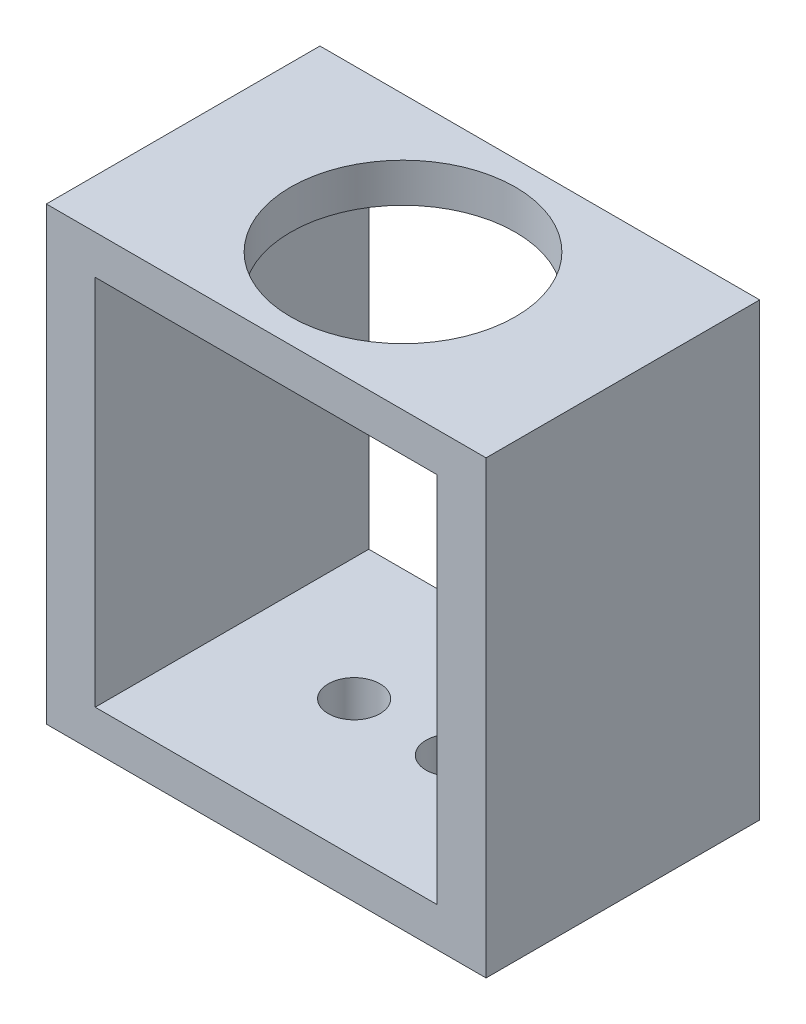
SolidWorks part; units mm, degrees
ref_plane "Front Plane" through (0, 0, 0) normal (0, 0, 1) x (1, 0, 0)
ref_plane "Top Plane" through (0, 0, 0) normal (0, 1, 0) x (1, 0, 0)
ref_plane "Right Plane" through (0, 0, 0) normal (1, 0, 0) x (0, 0, -1)
sketch "Sketch1" plane through (0, 0, 0) normal (0, 1, 0) x (1, 0, 0)
  line L0 (12.5, 14) -> (22.5, 14) construction
  line L1 (0, 0) -> (35, 0)
  line L2 (0, 0) -> (0, 28)
  line L3 (0, 28) -> (35, 28)
  line L4 (35, 0) -> (35, 28)
  line L5 (0, 14) -> (35, 14) construction
  line L6 (17.5, 28) -> (17.5, 0) construction
  circle A0 centre (12.5, 14) radius 2.65
  circle A1 centre (22.5, 14) radius 2.65
  dimension "D2" = 5.3
  dimension "D1" = 10
  dimension "D3" = 28
  dimension "D4" = 35
extrude "Boss-Extrude1" add sketch "Sketch1" along normal blind 4
sketch "Sketch2" plane through (0, 0, 0) normal (0, -1, 0) x (1, 0, 0)
  line L0 (35, -28) -> (0, -28) construction
  line L1 (0, 0) -> (-5, 0)
  line L2 (0, 0) -> (0, -28)
  line L3 (0, -28) -> (-5, -28)
  line L4 (-5, 0) -> (-5, -28)
  line L5 (35, 0) -> (40, 0)
  line L6 (35, 0) -> (35, -28)
  line L7 (35, -28) -> (40, -28)
  line L8 (40, 0) -> (40, -28)
  dimension "D1" = 5
  dimension "D2" = 5
extrude "Boss-Extrude2" add sketch "Sketch2" against normal blind 42.1
sketch "Sketch3" plane through (0, 42.1, 0) normal (0, 1, 0) x (1, 0, 0)
  line L0 (17.5, 28) -> (17.5, 0) construction
  line L1 (-5, 28) -> (40, 28)
  line L2 (-5, 28) -> (-5, 0)
  line L3 (-5, 0) -> (40, 0)
  line L4 (40, 28) -> (40, 0)
  line L5 (-5, 14) -> (40, 14) construction
  circle A0 centre (17.5, 14) radius 11.5
  dimension "D1" = 23
extrude "Boss-Extrude3" add sketch "Sketch3" along normal blind 4
